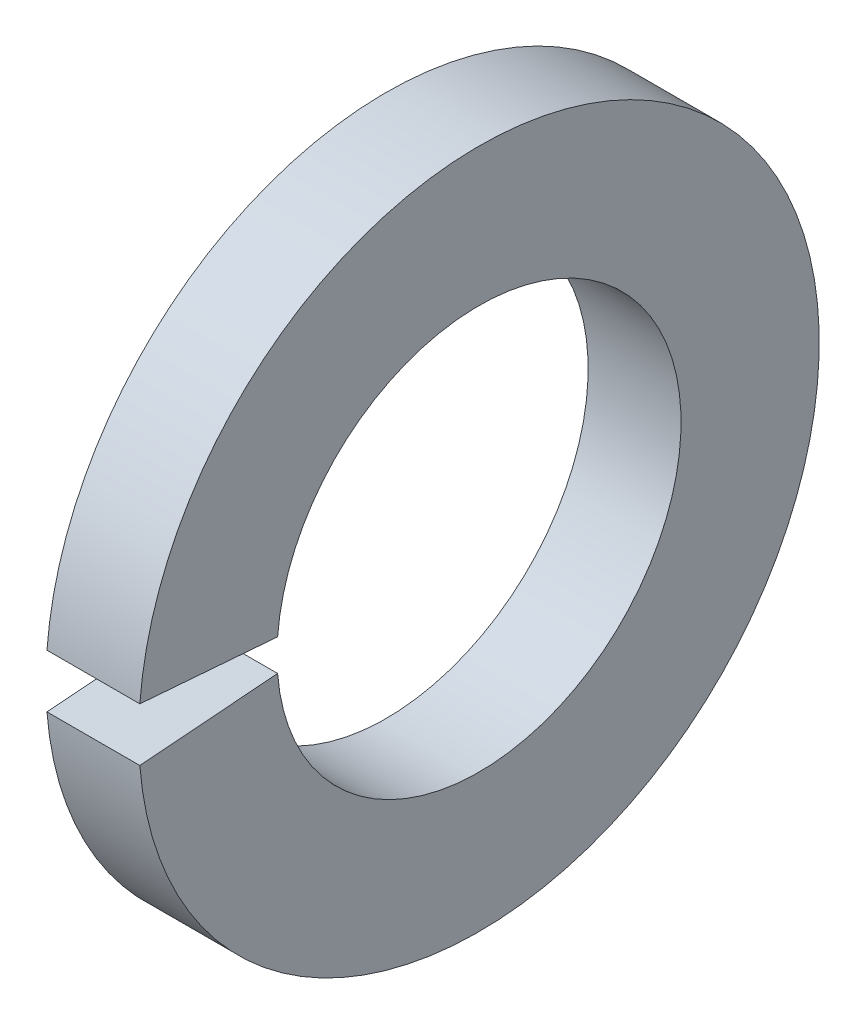
SolidWorks part; units mm, degrees
material "Chrome Stainless Steel"
ref_plane "Front Plane" through (0, 0, 0) normal (0, 0, 1) x (1, 0, 0)
ref_plane "Top Plane" through (0, 0, 0) normal (0, 1, 0) x (1, 0, 0)
ref_plane "Right Plane" through (0, 0, 0) normal (1, 0, 0) x (0, 0, -1)
ref_plane "Plane1" through (0, 0, 0) normal (0, 0.9969, 0.0785) x (-1, 0, 0)
sketch "Sketch1" plane through (0, 0, 0) normal (0, 0.9969, 0.0785) x (-1, 0, 0)
  line L0 (1.016, 3.7211) -> (0, 3.7211)
  line L1 (0, 3.7211) -> (0, 2.2098)
  line L2 (0, 2.2098) -> (1.016, 2.2098)
  line L3 (1.016, 2.2098) -> (1.016, 3.7211)
  line L4 (0, 0) -> (1.016, 0) construction
revolve "Revolve1" add sketch "Sketch1" angle 351 about L4
